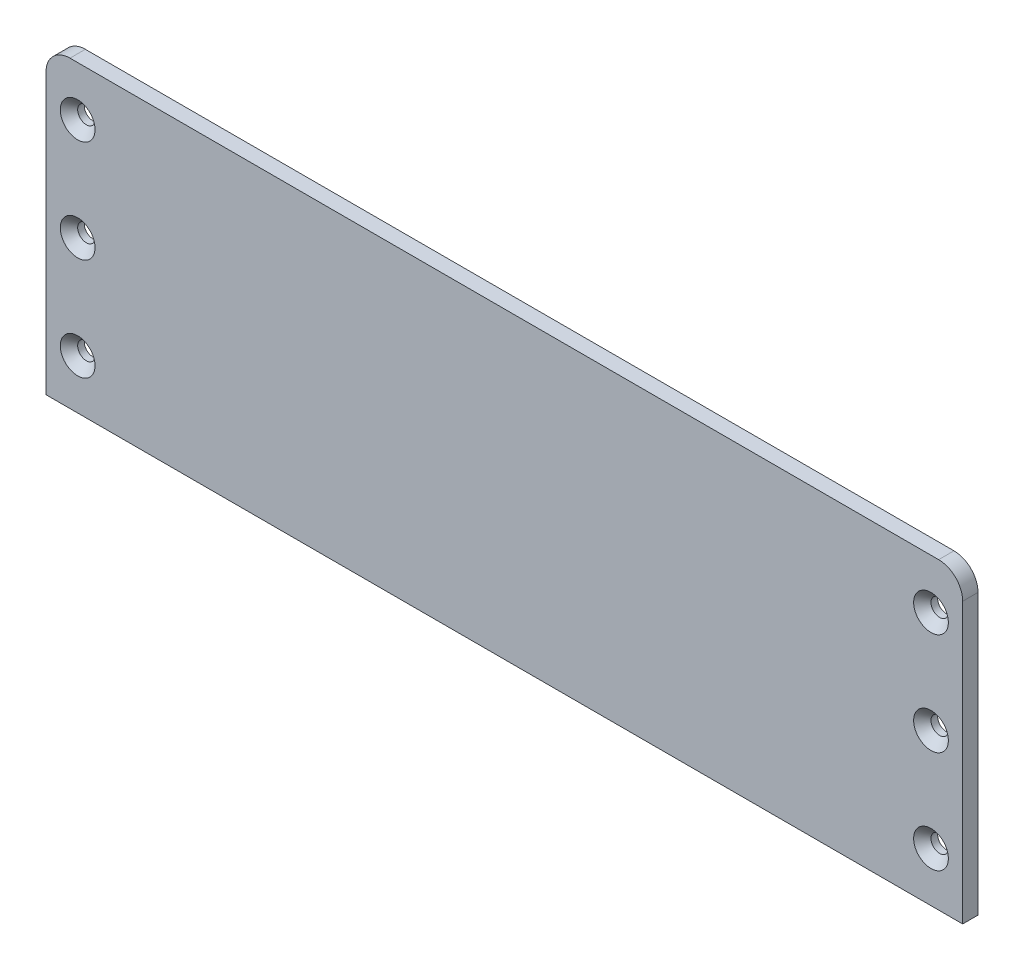
SolidWorks part; units mm, degrees
ref_plane "Front Plane" through (0, 0, 0) normal (0, 0, 1) x (1, 0, 0)
ref_plane "Top Plane" through (0, 0, 0) normal (0, 1, 0) x (1, 0, 0)
ref_plane "Right Plane" through (0, 0, 0) normal (1, 0, 0) x (0, 0, -1)
sketch "Sketch1" plane through (0, 0, 0) normal (0, 0, 1) x (1, 0, 0)
  line L1 (-90, -30) -> (90, -30)
  line L2 (-90, -30) -> (-90, 30)
  line L3 (-90, 30) -> (90, 30)
  line L4 (90, -30) -> (90, 30)
  line L5 (-90, -30) -> (90, 30) construction
  line L6 (-90, 30) -> (90, -30) construction
  point P0 (0, 0)
  dimension "D1" = 180
  dimension "D2" = 60
extrude "Boss-Extrude1" add sketch "Sketch1" along normal blind 3
fillet "Fillet1" radius 5 2 edges at (-90, 30, 1.5) (90, 30, 1.5)
sketch "Sketch2" plane through (0, 0, 3) normal (0, 0, 1) x (1, 0, 0)
  line L0 (90, -30) -> (90, 25) construction
  line L1 (-90, 25) -> (-90, -30) construction
  point P0 (-83.5, 20)
  point P2 (-83.5, 0)
  point P4 (-83.5, -20)
  point P6 (83.5, 20)
  point P8 (83.5, 0)
  point P10 (83.5, -20)
  dimension "D1" = 20
  dimension "D2" = 20
  dimension "D3" = 20
  dimension "D4" = 20
  dimension "D5" = 6.5
  dimension "D6" = 6.5
hole_wizard "CSK for M3 Flat Head Machine Screw1" positions "Sketch2" profile "Sketch3" countersink size "M3" standard "ANSI Metric" end condition through all
sketch "Sketch3" plane through (-83.5, 20, 3) normal (1, 0, 0) x (0, -1, 0)
  line L0 (0, 0) -> (0, 3)
  line L1 (0, 3) -> (1.7, 3)
  line L2 (1.7, 3) -> (1.7, 1.7)
  line L3 (1.7, 1.7) -> (3.4, 0)
  line L5 (3.4, 0) -> (0, 0)
  line L6 (-1.7, 1.7) -> (-3.4, 0) construction
  line L11 (0, -6.35) -> (0, 107.95) construction
  dimension "Thru Hole Dia." = 3.4
  dimension "Thru Hole Depth" = 3
  dimension "Near C'Sink Dia." = 6.8
  dimension "Near C'Sink Angle" = 90
sketch "Sketch4" plane through (0, 0, 3) normal (0, 0, 1) x (1, 0, 0)
  line L0 (85, 29.7) -> (-85, 29.7)
  line L1 (-89.7, 25) -> (-89.7, -29.7)
  line L2 (-89.7, -29.7) -> (89.7, -29.7)
  line L3 (89.7, -29.7) -> (89.7, 25)
  line L4 (85, 30) -> (-85, 30)
  line L5 (-90, 25) -> (-90, -30)
  line L6 (-90, -30) -> (90, -30)
  line L7 (90, -30) -> (90, 25)
  line L8 (85, 30) -> (-85, 30)
  line L9 (-90, 25) -> (-90, -30)
  line L10 (-90, -30) -> (90, -30)
  line L11 (90, -30) -> (90, 25)
  arc A0 (-85, 29.7) -> (-89.7, 25) centre (-85, 25) ccw
  arc A1 (89.7, 25) -> (85, 29.7) centre (85, 25) ccw
  arc A2 (-85, 30) -> (-90, 25) centre (-85, 25) ccw
  arc A3 (90, 25) -> (85, 30) centre (85, 25) ccw
  arc A4 (-85, 30) -> (-90, 25) centre (-85, 25) ccw
  arc A5 (90, 25) -> (85, 30) centre (85, 25) ccw
  dimension "D1" = 0
  dimension "D2" = 0.3
extrude "Cut-Extrude1" cut sketch "Sketch4" against normal up to next
sketch "Sketch5" plane through (0, 0, 0) normal (0, 0, -1) x (-1, 0, 0)
  line L4 (85, 29.7) -> (-85, 29.7)
  line L5 (-89.7, 25) -> (-89.7, -29.7)
  line L6 (-89.7, -29.7) -> (89.7, -29.7)
  line L7 (89.7, -29.7) -> (89.7, 25)
  line L8 (85, 29.7) -> (-85, 29.7)
  line L9 (-89.7, 25) -> (-89.7, -29.7)
  line L10 (-89.7, -29.7) -> (89.7, -29.7)
  line L11 (89.7, -29.7) -> (89.7, 25)
  arc A2 (-85, 29.7) -> (-89.7, 25) centre (-85, 25) ccw
  arc A3 (89.7, 25) -> (85, 29.7) centre (85, 25) ccw
  arc A4 (-85, 29.7) -> (-89.7, 25) centre (-85, 25) ccw
  arc A5 (89.7, 25) -> (85, 29.7) centre (85, 25) ccw
  dimension "D1" = 0
extrude "Cut-Extrude2" [suppressed] cut sketch "Sketch5" against normal blind 0.3
